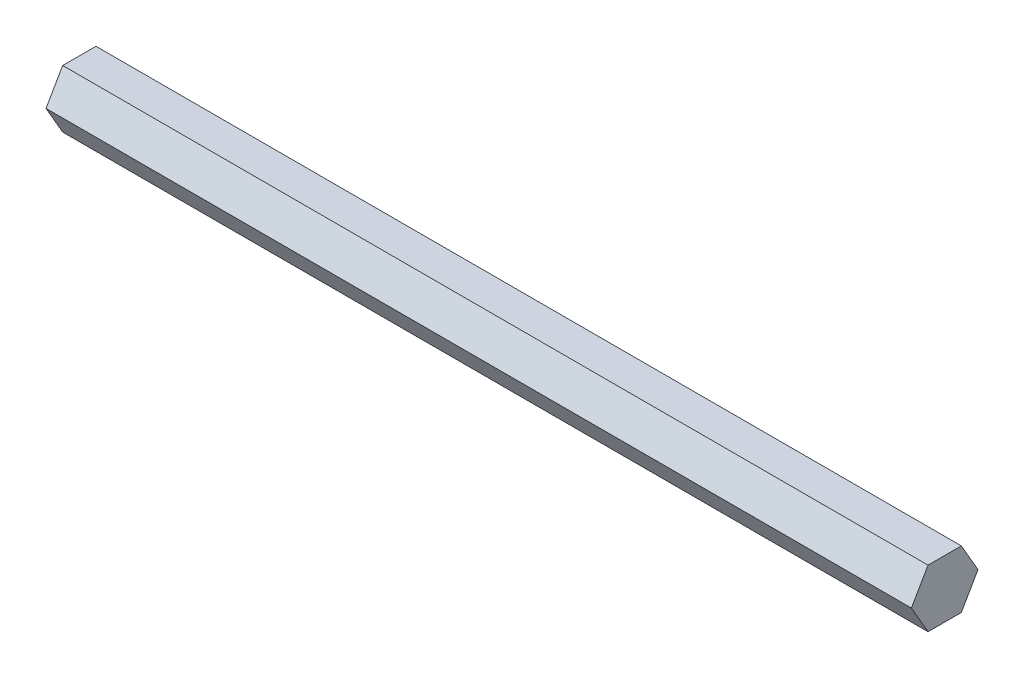
SolidWorks part; units mm, degrees
ref_plane "Front Plane" through (0, 0, 0) normal (0, 0, 1) x (1, 0, 0)
ref_plane "Top Plane" through (0, 0, 0) normal (0, 1, 0) x (1, 0, 0)
ref_plane "Right Plane" through (0, 0, 0) normal (1, 0, 0) x (0, 0, -1)
ref_plane "Plane1" through (0, 0, 0) normal (-1, 0, 0) x (0, -1, 0)
sketch "Sketch1" plane through (0, 0, 0) normal (-1, 0, 0) x (0, -1, 0)
  line L0 (-6.35, 3.6662) -> (-6.35, -3.6662)
  line L1 (-6.35, -3.6662) -> (0, -7.3323)
  line L2 (0, -7.3323) -> (6.35, -3.6662)
  line L3 (6.35, -3.6662) -> (6.35, 3.6662)
  line L4 (6.35, 3.6662) -> (0, 7.3323)
  line L5 (0, 7.3323) -> (-6.35, 3.6662)
extrude "Boss-Extrude1" add sketch "Sketch1" against normal blind 190.5
